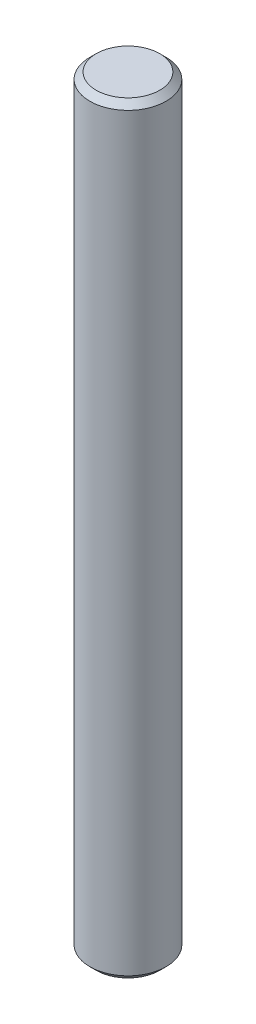
SolidWorks part; units mm, degrees
material "AISI 304"
ref_plane "Front Plane" through (0, 0, 0) normal (0, 0, 1) x (1, 0, 0)
ref_plane "Top Plane" through (0, 0, 0) normal (0, 1, 0) x (1, 0, 0)
ref_plane "Right Plane" through (0, 0, 0) normal (1, 0, 0) x (0, 0, -1)
sketch "Sketch2" plane through (0, 0, 0) normal (0, 1, 0) x (1, 0, 0)
  circle A0 centre (0, 0) radius 1.5
  dimension "D1" = 3
extrude "Boss-Extrude1" add sketch "Sketch2" along normal blind 30
chamfer "Chamfer1" distance 0.25 angle 45 2 edges at (0, 0, 1.5) (0, 30, 1.5)
